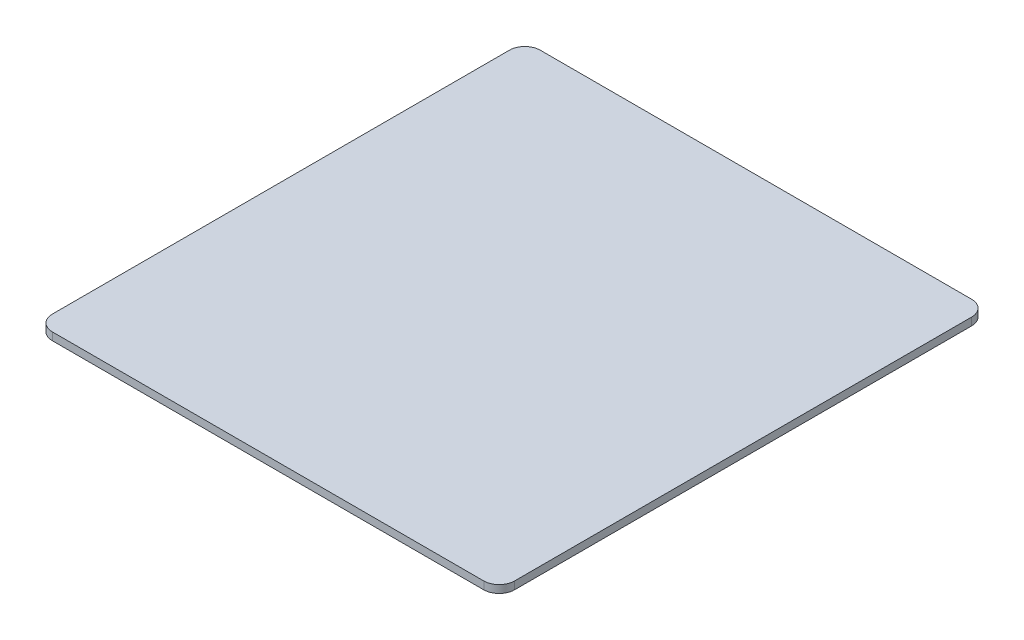
SolidWorks part; units mm, degrees
ref_plane "Front Plane" through (0, 0, 0) normal (0, 0, 1) x (1, 0, 0)
ref_plane "Top Plane" through (0, 0, 0) normal (0, 1, 0) x (1, 0, 0)
ref_plane "Right Plane" through (0, 0, 0) normal (1, 0, 0) x (0, 0, -1)
sketch "Sketch1" plane through (0, 0, 0) normal (0, 1, 0) x (1, 0, 0)
  line L1 (-90, -95) -> (90, -95)
  line L2 (-90, -95) -> (-90, 95)
  line L3 (-90, 95) -> (90, 95)
  line L4 (90, -95) -> (90, 95)
  line L5 (-90, -95) -> (90, 95) construction
  line L6 (-90, 95) -> (90, -95) construction
  point P0 (0, 0)
  dimension "D1" = 180
  dimension "D2" = 190
extrude "Boss-Extrude1" add sketch "Sketch1" against normal blind 3
fillet "Fillet1" radius 6 4 edges at (-90, -1.5, -95) (-90, -1.5, 95) (90, -1.5, 95) (90, -1.5, -95)
